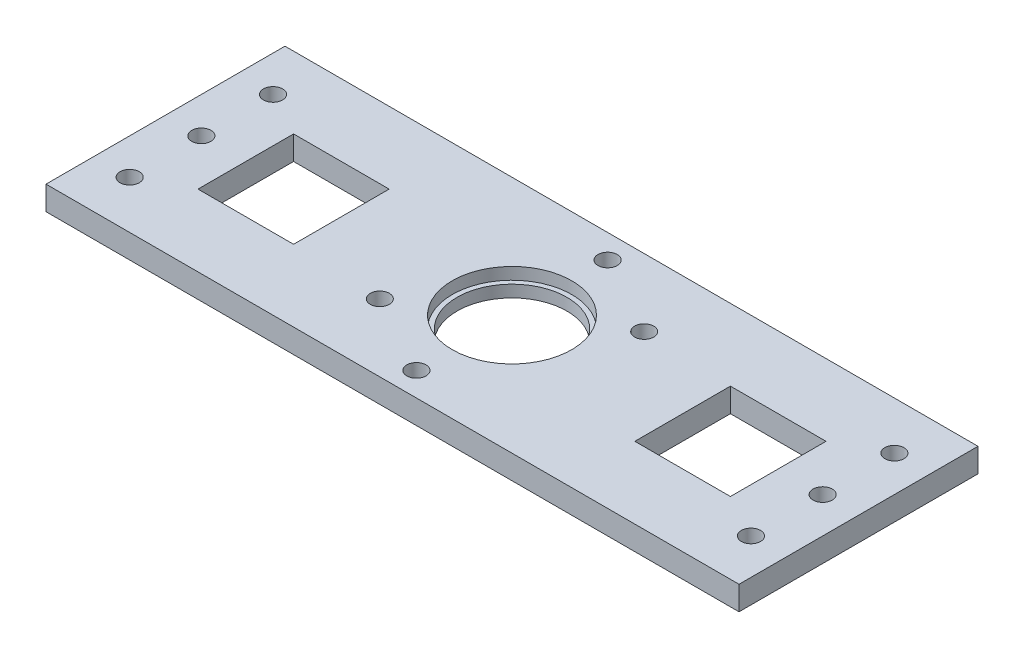
SolidWorks part; units mm, degrees
ref_plane "Front Plane" through (0, 0, 0) normal (0, 0, 1) x (1, 0, 0)
ref_plane "Top Plane" through (0, 0, 0) normal (0, 1, 0) x (1, 0, 0)
ref_plane "Right Plane" through (0, 0, 0) normal (1, 0, 0) x (0, 0, -1)
sketch "Sketch1" plane through (0, 0, 0) normal (0, 1, 0) x (1, 0, 0)
  line L1 (-92.075, -31.75) -> (92.075, -31.75)
  line L2 (-92.075, -31.75) -> (-92.075, 31.75)
  line L3 (-92.075, 31.75) -> (92.075, 31.75)
  line L4 (92.075, -31.75) -> (92.075, 31.75)
  line L5 (-92.075, -31.75) -> (92.075, 31.75) construction
  line L6 (-92.075, 31.75) -> (92.075, -31.75) construction
  point P0 (0, 0)
  dimension "D1" = 184.15
  dimension "D2" = 63.5
extrude "Boss-Extrude1" add sketch "Sketch1" along normal blind 6.35
sketch "Sketch2" plane through (0, 6.35, 0) normal (0, 1, 0) x (1, 0, 0)
  line L0 (-41.275, -31.75) -> (-41.275, 31.75)
  line L1 (-92.075, -31.75) -> (92.075, -31.75) construction
  line L2 (92.075, 31.75) -> (-92.075, 31.75) construction
  line L3 (-92.075, 31.75) -> (-92.075, -31.75) construction
  line L4 (41.275, 31.75) -> (41.275, -31.75)
  line L5 (92.075, -31.75) -> (92.075, 31.75) construction
  dimension "D1" = 50.8
  dimension "D2" = 50.8
sketch "Sketch3" plane through (0, 6.35, 0) normal (0, 1, 0) x (1, 0, 0)
  circle A0 centre (0, 0) radius 14.605
  dimension "D1" = 29.21
extrude "Cut-Extrude1" cut sketch "Sketch3" against normal through all
sketch "Sketch6" plane through (0, 0, 31.75) normal (0, 0, 1) x (1, 0, 0)
  line L0 (-41.275, 6.35) -> (-41.275, 0)
  line L1 (-92.075, 0) -> (92.075, 0) construction
sketch "Sketch7" plane through (0, 0, 0) normal (0, -1, 0) x (1, 0, 0)
  line L0 (-41.275, 31.75) -> (-41.275, -31.75)
  line L1 (92.075, -31.75) -> (-92.075, -31.75) construction
sketch "Sketch8" plane through (0, 0, 31.75) normal (0, 0, 1) x (1, 0, 0)
  line L0 (41.275, 6.35) -> (41.275, 0)
  line L1 (-92.075, 0) -> (92.075, 0) construction
  dimension "D1" = 82.55
  dimension "D2" = 82.55
sketch "Sketch9" plane through (0, 0, 0) normal (0, -1, 0) x (1, 0, 0)
  line L0 (41.275, 31.75) -> (41.275, -31.75)
  line L1 (92.075, -31.75) -> (-92.075, -31.75) construction
hole_wizard "#10 Clearance Hole1" positions "Sketch22" profile "Sketch23" hole size "#10" standard "ANSI Inch" end condition through all
sketch "Sketch22" plane through (0, 0, 0) normal (0, -1, 0) x (-1, 0, 0)
  point P0 (0, -25.4)
  point P2 (0, 25.4)
  dimension "D1" = 25.4
  dimension "D2" = 25.4
sketch "Sketch23" plane through (0, 0, 25.4) normal (1, 0, 0) x (0, 0, -1)
  line L0 (0, 0) -> (0, 6.35)
  line L1 (0, 6.35) -> (2.5527, 6.35)
  line L2 (2.5527, 6.35) -> (2.5527, 0)
  line L5 (2.5527, 0) -> (0, 0)
  line L11 (0, -6.35) -> (0, 107.95) construction
  dimension "Thru Hole Dia." = 5.1054
  dimension "Thru Hole Depth" = 6.35
hole_wizard "Ø6.5 (6.5) Diameter Hole3" positions "Sketch24" profile "Sketch25" hole size "Ø6.5" standard "ANSI Metric" end condition through all
sketch "Sketch24" plane through (0, 0, 0) normal (0, -1, 0) x (-1, 0, 0)
  line L0 (41.275, -31.75) -> (41.275, 31.75) construction
  line L1 (-41.275, 31.75) -> (-41.275, -31.75) construction
  point P0 (58.039, 0)
  point P2 (-58.039, 0)
  dimension "D1" = 16.764
  dimension "D2" = 16.764
sketch "Sketch25" plane through (-58.039, 0, 0) normal (1, 0, 0) x (0, 0, -1)
  line L0 (0, 0) -> (0, 6.35)
  line L1 (0, 6.35) -> (3.25, 6.35)
  line L2 (3.25, 6.35) -> (3.25, 0)
  line L5 (3.25, 0) -> (0, 0)
  line L11 (0, -6.35) -> (0, 107.95) construction
  dimension "Thru Hole Dia." = 6.5
  dimension "Thru Hole Depth" = 6.35
sketch "Sketch29" plane through (0, 6.35, 0) normal (0, 1, 0) x (1, 0, 0)
  circle A0 centre (0, 0) radius 15.875
extrude "Cut-Extrude5" cut sketch "Sketch29" against normal blind 3.175
hole_wizard "#10 Clearance Hole2" positions "Sketch32" profile "Sketch31" hole size "#10" standard "ANSI Inch" end condition through all
sketch "Sketch32" plane through (0, 6.35, 0) normal (0, 1, 0) x (1, 0, 0)
  line L0 (92.075, 31.75) -> (-92.075, 31.75) construction
  line L1 (-92.075, 31.75) -> (-92.075, -31.75) construction
  line L2 (-92.075, -31.75) -> (92.075, -31.75) construction
  line L3 (92.075, -31.75) -> (92.075, 31.75) construction
  point P0 (-82.55, 19.05)
  point P2 (-82.55, -19.05)
  point P4 (82.55, -19.05)
  point P6 (82.55, 19.05)
  point P17 (-82.55, 0)
  point P19 (82.55, 0)
  dimension "D1" = 12.7
  dimension "D2" = 9.525
  dimension "D3" = 9.525
  dimension "D4" = 12.7
  dimension "D5" = 9.525
  dimension "D6" = 12.7
  dimension "D7" = 9.525
  dimension "D8" = 12.7
sketch "Sketch31" plane through (-82.55, 6.35, -19.05) normal (1, 0, 0) x (0, 0, 1)
  line L0 (0, 0) -> (0, 6.35)
  line L1 (0, 6.35) -> (2.5527, 6.35)
  line L2 (2.5527, 6.35) -> (2.5527, 0)
  line L5 (2.5527, 0) -> (0, 0)
  line L11 (0, -6.35) -> (0, 107.95) construction
  dimension "Thru Hole Dia." = 5.1054
  dimension "Thru Hole Depth" = 6.35
sketch "Sketch36" plane through (0, 0, 0) normal (0, -1, 0) x (1, 0, 0)
  line L0 (-92.075, 31.75) -> (92.075, 31.75) construction
  line L1 (92.075, -31.75) -> (-92.075, -31.75) construction
  circle A0 centre (-21.3292, 13.7922) radius 2.54
  circle A1 centre (21.3292, -13.7922) radius 2.54
  dimension "D1" = 25.4
  dimension "D2" = 5.08
  dimension "D4" = 5.08
  dimension "D3" = 17.9578
  dimension "D5" = 50.8
  dimension "D6" = 17.9578
extrude "Cut-Extrude6" cut sketch "Sketch36" against normal through all
sketch "Sketch37" plane through (0, 6.35, 0) normal (0, 1, 0) x (1, 0, 0)
  line L1 (-70.739, 12.7) -> (-45.339, 12.7)
  line L2 (-70.739, 12.7) -> (-70.739, -12.7)
  line L3 (-70.739, -12.7) -> (-45.339, -12.7)
  line L4 (-45.339, 12.7) -> (-45.339, -12.7)
  line L5 (-70.739, 12.7) -> (-45.339, -12.7) construction
  line L6 (-70.739, -12.7) -> (-45.339, 12.7) construction
  point P0 (-58.039, 0)
extrude "Cut-Extrude7" cut sketch "Sketch37" against normal through all
sketch "Sketch38" plane through (0, 6.35, 0) normal (0, 1, 0) x (1, 0, 0)
  line L1 (45.339, 12.7) -> (70.739, 12.7)
  line L2 (45.339, 12.7) -> (45.339, -12.7)
  line L3 (45.339, -12.7) -> (70.739, -12.7)
  line L4 (70.739, 12.7) -> (70.739, -12.7)
  line L5 (45.339, 12.7) -> (70.739, -12.7) construction
  line L6 (45.339, -12.7) -> (70.739, 12.7) construction
  point P0 (58.039, 0)
extrude "Cut-Extrude8" cut sketch "Sketch38" against normal through all
